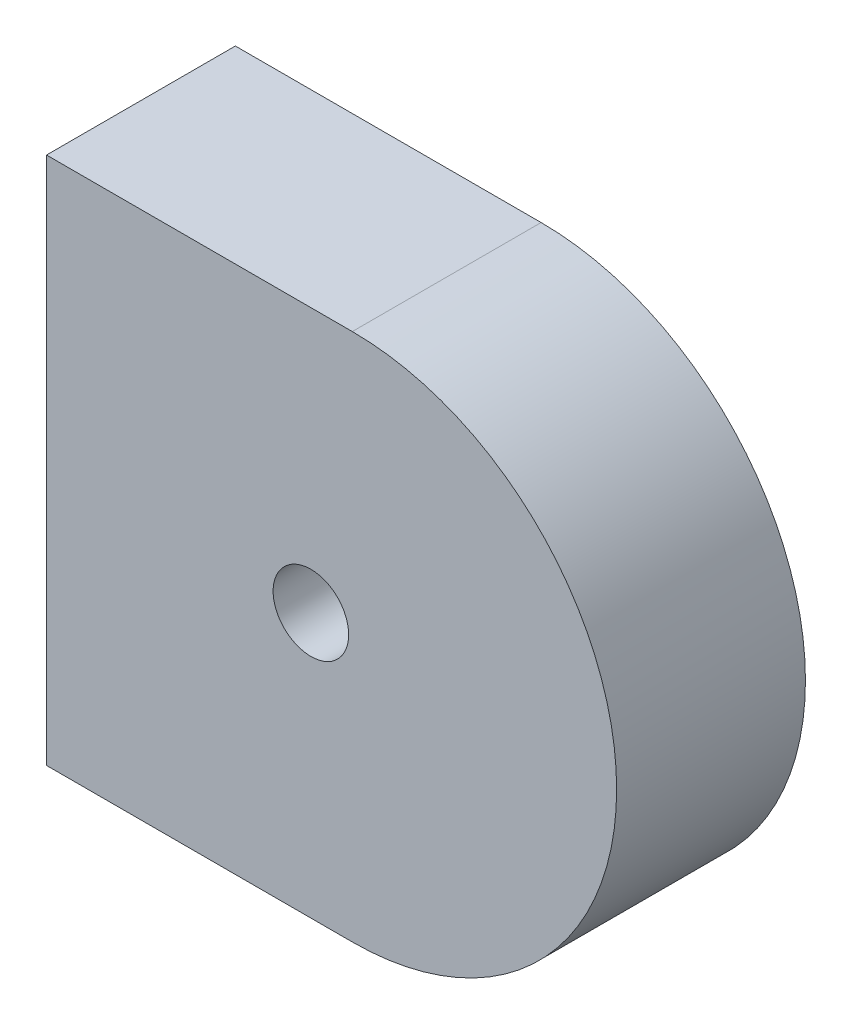
SolidWorks part; units mm, degrees
material "1.4000 (X6Cr13)"
ref_plane "Plan de face" through (0, 0, 0) normal (0, 0, 1) x (1, 0, 0)
ref_plane "Plan de dessus" through (0, 0, 0) normal (0, 1, 0) x (1, 0, 0)
ref_plane "Plan de droite" through (0, 0, 0) normal (1, 0, 0) x (0, 0, -1)
sketch "Esquisse1" plane through (0, 0, 0) normal (0, 0, 1) x (1, 0, 0)
  line L0 (0, 14) -> (0, 0)
  line L1 (0, 0) -> (8.0968, 0)
  line L2 (0, 14) -> (8.0968, 14)
  arc A0 (8.0968, 14) -> (8.0968, 0) centre (8.0968, 7) cw
  dimension "D1" = 14
extrude "Boss.-Extru.1" add sketch "Esquisse1" along normal blind 5
hole_wizard "Trou de passage d'axe 3/322" positions "Esquisse3D3" profile "Esquisse3" hole size "3/32" standard "PCS" end condition through all
sketch3d "Esquisse3D3"
  line L0 (8.0968, 14, 5) -> (0, 14, 5) construction
  line L1 (0, 14, 5) -> (0, 0, 5) construction
  point P0 (7, 7, 5)
  dimension "D1" = 7
  dimension "D2" = 7
sketch "Esquisse3" plane through (7, 7, 5) normal (1, 0, 0) x (0, -1, 0)
  line L0 (0, 0) -> (0, 5)
  line L1 (0, 5) -> (1, 5)
  line L2 (1, 5) -> (1, 0)
  line L5 (1, 0) -> (0, 0)
  line L11 (0, -6.35) -> (0, 107.95) construction
  dimension "Diamètre du perçage jusqu'au prochain" = 2
  dimension "Profondeur du perçage jusqu'au prochain" = 5
